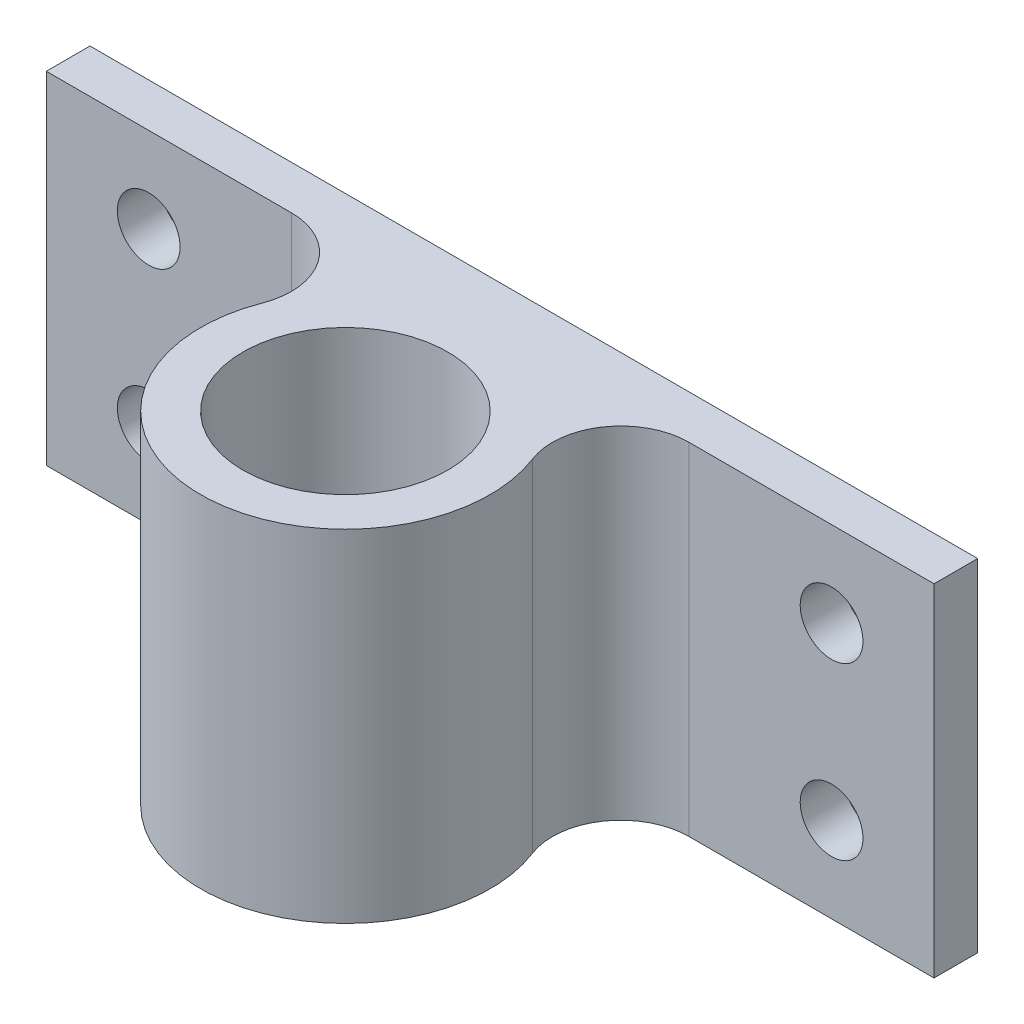
SolidWorks part; units mm, degrees
ref_plane "Front Plane" through (0, 0, 0) normal (0, 0, 1) x (1, 0, 0)
ref_plane "Top Plane" through (0, 0, 0) normal (0, 1, 0) x (1, 0, 0)
ref_plane "Right Plane" through (0, 0, 0) normal (1, 0, 0) x (0, 0, -1)
sketch "Sketch3" plane through (0, 0, 0) normal (0, 1, 0) x (1, 0, 0)
  line L0 (-325, 106) -> (-141.1406, 106)
  line L1 (0, 0) -> (0, 238.3893) construction
  line L3 (-325, 138) -> (325, 138)
  line L4 (-325, 106) -> (-325, 138)
  line L5 (325, 106) -> (325, 138)
  line L6 (141.1406, 106) -> (325, 106)
  line L8 (-325, 106) -> (325, 106) construction
  arc A0 (-98.9348, 38.0513) -> (98.9348, 38.0513) centre (0, 0) ccw
  circle A1 centre (0, 0) radius 75
  arc A2 (-98.9348, 38.0513) -> (-145.6022, 106) centre (-145.6022, 56) ccw
  arc A3 (98.9348, 38.0513) -> (145.6022, 106) centre (145.6022, 56) cw
  point P7 (0, 106)
  dimension "D1" = 212
  dimension "D2" = 150
  dimension "D5" = 100
  dimension "D3" = 650
  dimension "D4" = 32
extrude "Boss-Extrude1" add sketch "Sketch3" along normal blind 250
sketch "Sketch4" plane through (0, 0, -138) normal (0, 0, -1) x (-1, 0, 0)
  line L0 (0, 0) -> (0, 250) construction
  line L1 (325, 250) -> (-325, 250) construction
  line L2 (0, 187.5) -> (-325, 187.5) construction
  line L3 (-325, 250) -> (-325, 0) construction
  line L4 (0, 125) -> (330.0731, 125) construction
  circle A0 centre (-250, 187.5) radius 22.9841
  circle A1 centre (250, 187.5) radius 22.9841
  circle A2 centre (250, 62.5) radius 22.9841
  circle A3 centre (-250, 62.5) radius 22.9841
  dimension "D2" = 500
  dimension "D1" = 62.5
extrude "Cut-Extrude1" cut sketch "Sketch4" against normal through all
